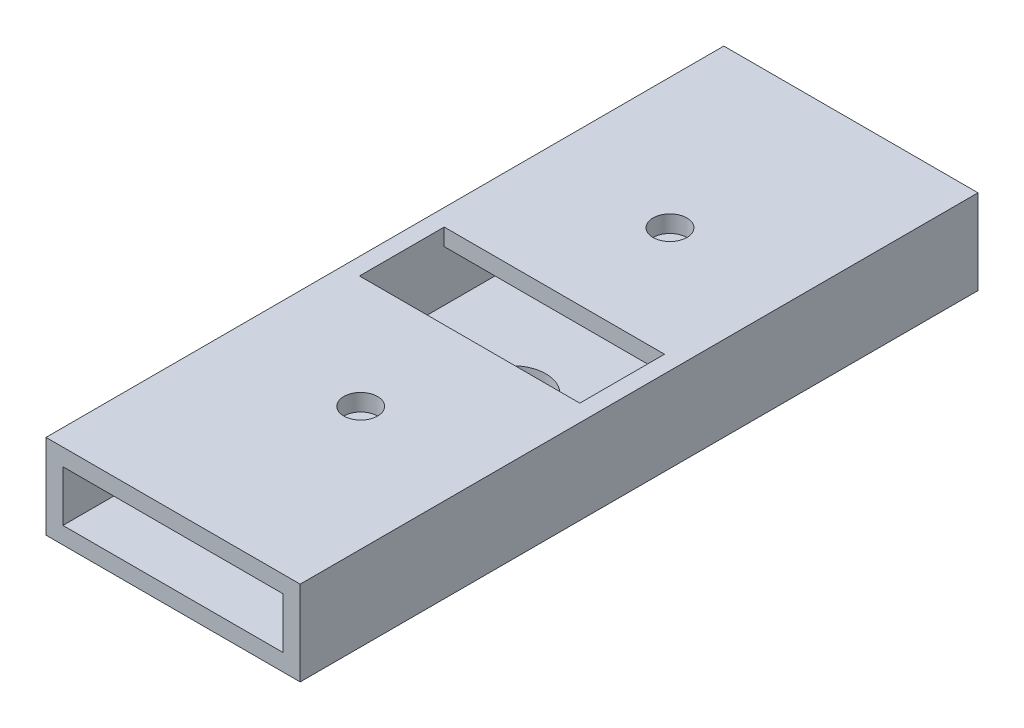
SolidWorks part; units mm, degrees
ref_plane "Plano frontal" through (0, 0, 0) normal (0, 0, 1) x (1, 0, 0)
ref_plane "Plano superior" through (0, 0, 0) normal (0, 1, 0) x (1, 0, 0)
ref_plane "Plano direito" through (0, 0, 0) normal (1, 0, 0) x (0, 0, -1)
sketch "Esboço1" plane through (0, 0, 0) normal (0, 0, 1) x (1, 0, 0)
  line L1 (0, 0) -> (30, 0)
  line L2 (0, 0) -> (0, 10)
  line L3 (0, 10) -> (30, 10)
  line L4 (30, 0) -> (30, 10)
  line L5 (2, 2) -> (28, 2)
  line L6 (2, 2) -> (2, 8)
  line L7 (2, 8) -> (28, 8)
  line L8 (28, 2) -> (28, 8)
  dimension "D1" = 30
  dimension "D2" = 10
  dimension "D3" = 6
  dimension "D4" = 26
extrude "Ressalto-extrusão1" add sketch "Esboço1" along normal blind 80
sketch "Esboço2" plane through (0, 10, 0) normal (0, 1, 0) x (1, 0, 0)
  circle A0 centre (15, -40) radius 4
extrude "Corte-extrusão1" cut sketch "Esboço2" against normal blind 10
sketch "Esboço3" plane through (0, 10, 0) normal (0, 1, 0) x (1, 0, 0)
  line L1 (2, -45) -> (28, -45)
  line L2 (2, -45) -> (2, -35)
  line L3 (2, -35) -> (28, -35)
  line L4 (28, -45) -> (28, -35)
  line L5 (2, -45) -> (28, -35) construction
  line L6 (2, -35) -> (28, -45) construction
  point P0 (15, -40)
  dimension "D1" = 10
  dimension "D2" = 26
extrude "Corte-extrusão2" cut sketch "Esboço3" against normal blind 2
sketch "Esboço5" plane through (0, 0, 0) normal (0, -1, 0) x (-1, 0, 0)
  line L0 (-15, -40) -> (-15, -58.5)
  line L2 (-2, -53.5) -> (-28, -53.5)
  line L3 (-2, -53.5) -> (-2, -63.5)
  line L4 (-2, -63.5) -> (-28, -63.5)
  line L5 (-28, -53.5) -> (-28, -63.5)
  line L6 (-2, -53.5) -> (-28, -63.5) construction
  line L7 (-2, -63.5) -> (-28, -53.5) construction
  dimension "D1" = 18.5
  dimension "D2" = 10
  dimension "D3" = 26
ref_plane "Plano1" through (0, 0, 40) normal (0, 0, -1) x (-1, 0, 0)
extrude "Corte-extrusão3" cut sketch "Esboço5" against normal blind 2
sketch "Esboço6" plane through (0, 8, 0) normal (0, -1, 0) x (-1, 0, 0)
  circle A0 centre (-15.392, -58.25) radius 2
  circle A1 centre (-15, -40) radius 4 construction
  dimension "D1" = 18.25
  dimension "D2" = 4
extrude "Corte-extrusão4" cut sketch "Esboço6" against normal blind 2
mirror "Espelhar6" about plane through (0, 0, 40) normal (0, 0, -1) of "Corte-extrusão4", "Corte-extrusão3"
ref_plane "Plano2" through (15, 0, 0) normal (-1, 0, 0) x (0, 0, 1)
sketch "Esboço7" plane through (0, 2, 0) normal (0, 1, 0) x (1, 0, 0)
  circle A0 centre (24.53, -40) radius 1.25
  circle A1 centre (15, -40) radius 4 construction
  dimension "D1" = 9.53
  dimension "D2" = 2.5
extrude "Corte-extrusão5" cut sketch "Esboço7" against normal blind 2
mirror "Espelhar7" about plane through (15, 0, 0) normal (-1, 0, 0) of "Corte-extrusão5"
